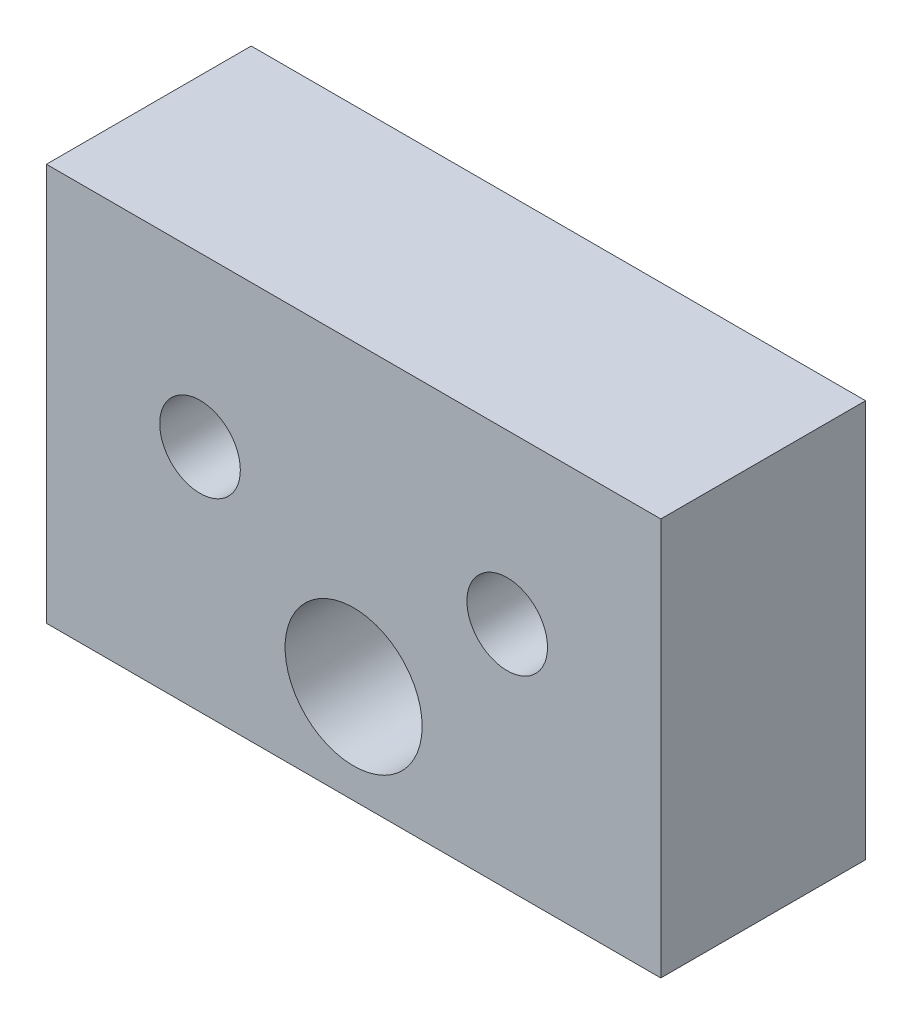
SolidWorks part; units mm, degrees
material "Acrylic (Medium-high impact)"
ref_plane "Front Plane" through (0, 0, 0) normal (0, 0, 1) x (1, 0, 0)
ref_plane "Top Plane" through (0, 0, 0) normal (0, 1, 0) x (1, 0, 0)
ref_plane "Right Plane" through (0, 0, 0) normal (1, 0, 0) x (0, 0, -1)
sketch "Sketch1" plane through (0, 0, 0) normal (0, 0, 1) x (1, 0, 0)
  line L2 (38.1, -12.224) -> (38.1, 12.224)
  line L4 (-38.1, -12.224) -> (-38.1, 12.224)
  line L8 (-38.1, -12.224) -> (38.1, -12.224)
  line L11 (-38.1, 37.084) -> (-38.1, 12.224)
  line L12 (38.1, 12.224) -> (38.1, 37.084)
  line L13 (-38.1, 37.084) -> (-38.1, 49.2259)
  line L14 (-38.1, 37.084) -> (38.1, 37.084)
  line L16 (-38.1, 49.2259) -> (38.1, 49.2259)
  line L18 (38.1, 37.084) -> (38.1, 49.2259)
  circle A0 centre (0, 0) radius 8.5
  circle A1 centre (19.05, 16.256) radius 5
  circle A2 centre (-19.05, 16.256) radius 5
  point P0 (0, 0)
  point P6 (-38.1, 0)
  dimension "D3" = 17
  dimension "D4" = 10
  dimension "D1" = 76.2
  dimension "D2" = 20.828
  dimension "D5" = 19.05
  dimension "D6" = 16.256
  dimension "D7" = 19.05
  dimension "D8" = 61.4499
  dimension "D9" = 76.2
extrude "Boss-Extrude2" add sketch "Sketch1" along normal mid plane 25.4 contours L14 L11 L4 L8 L2 L12 A2 A1 A0
